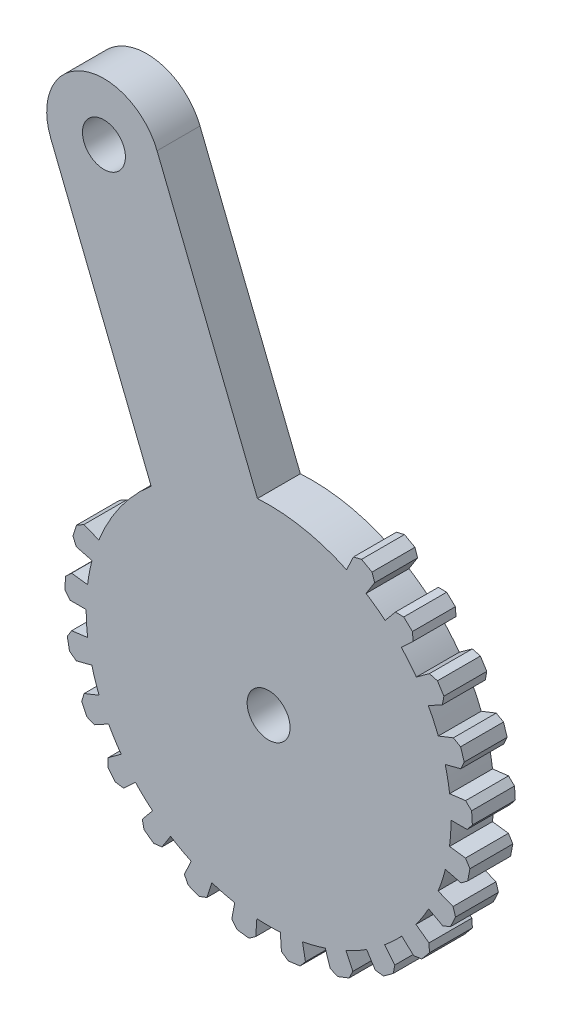
SolidWorks part; units mm, degrees
ref_plane "Front Plane" through (0, 0, 0) normal (0, 0, 1) x (1, 0, 0)
ref_plane "Top Plane" through (0, 0, 0) normal (0, 1, 0) x (1, 0, 0)
ref_plane "Right Plane" through (0, 0, 0) normal (1, 0, 0) x (0, 0, -1)
sketch "Sketch1" plane through (0, 0, 0) normal (0, 0, 1) x (1, 0, 0)
  line L4 (0, 0) -> (-4.7333, 11.8389) construction
  line L5 (0, 0) -> (-11.5084, 28.7847) construction
  line L6 (-8.2085, 9.7562) -> (-15.2225, 27.2997)
  line L7 (-0.7802, 12.7261) -> (-7.7942, 30.2696)
  line L9 (-6.862, 12.482) -> (-6.865, 12.4874) construction
  line L11 (-9.7506, 10.3833) -> (-9.7548, 10.3878) construction
  line L12 (-12.0265, 7.6322) -> (-12.0317, 7.6355) construction
  line L13 (-13.5467, 4.4016) -> (-13.5526, 4.4035) construction
  line L14 (-14.2157, 0.8944) -> (-14.2219, 0.8948) construction
  line L16 (5.4488, 11.5271) -> (5.9296, 12.5441)
  line L17 (7.4141, 11.728) -> (7.2288, 12.2804)
  line L18 (5.9296, 12.5441) -> (6.4953, 12.6836)
  line L19 (6.813, 10.7771) -> (7.4141, 11.728)
  line L20 (6.4953, 12.6836) -> (7.2288, 12.2804)
  line L22 (8.1443, 9.8098) -> (8.8629, 10.6754)
  line L23 (10.0978, 9.5157) -> (10.0557, 10.0968)
  line L24 (8.8629, 10.6754) -> (9.4455, 10.6698)
  line L25 (9.2791, 8.7442) -> (10.0978, 9.5157)
  line L26 (9.4455, 10.6698) -> (10.0557, 10.0968)
  line L28 (10.328, 7.4762) -> (11.2393, 8.1359)
  line L29 (12.1471, 6.7055) -> (12.2507, 7.2789)
  line L30 (11.2393, 8.1359) -> (11.8022, 7.9856)
  line L31 (11.1622, 6.1619) -> (12.1471, 6.7055)
  line L32 (11.8022, 7.9856) -> (12.2507, 7.2789)
  line L34 (11.8628, 4.6729) -> (12.9095, 5.0852)
  line L35 (13.433, 3.474) -> (13.676, 4.0036)
  line L36 (12.9095, 5.0852) -> (13.4174, 4.7996)
  line L37 (12.3439, 3.1923) -> (13.433, 3.474)
  line L38 (13.4174, 4.7996) -> (13.676, 4.0036)
  line L40 (12.6522, 1.5759) -> (13.7686, 1.715)
  line L41 (13.875, 0.0242) -> (14.242, 0.4767)
  line L42 (13.7686, 1.715) -> (14.1895, 1.312)
  line L43 (12.75, 0.0223) -> (13.875, 0.0242)
  line L44 (14.1895, 1.312) -> (14.242, 0.4767)
  line L46 (12.6467, -1.6201) -> (13.7625, -1.763)
  line L47 (13.4451, -3.4271) -> (13.9131, -3.0801)
  line L48 (13.7625, -1.763) -> (14.07, -2.258)
  line L49 (12.355, -3.1492) -> (13.4451, -3.4271)
  line L50 (14.07, -2.258) -> (13.9131, -3.0801)
  line L52 (11.8464, -4.7143) -> (12.8917, -5.1302)
  line L53 (12.1704, -6.6631) -> (12.71, -6.4434)
  line L54 (12.8917, -5.1302) -> (13.0664, -5.6861)
  line L55 (11.1836, -6.1228) -> (12.1704, -6.6631)
  line L56 (13.0664, -5.6861) -> (12.71, -6.4434)
  line L58 (10.3019, -7.5123) -> (11.2109, -8.1751)
  line L59 (10.131, -9.4804) -> (10.7083, -9.4018)
  line L60 (11.2109, -8.1751) -> (11.2418, -8.7569)
  line L61 (9.3096, -8.7117) -> (10.131, -9.4804)
  line L62 (11.2418, -8.7569) -> (10.7083, -9.4018)
  line L64 (8.11, -9.8382) -> (8.8256, -10.7063)
  line L65 (7.455, -11.7021) -> (8.0338, -11.7695)
  line L66 (8.8256, -10.7063) -> (8.7109, -11.2775)
  line L67 (6.8506, -10.7532) -> (7.455, -11.7021)
  line L68 (8.7109, -11.2775) -> (8.0338, -11.7695)
  line L70 (5.4085, -11.546) -> (5.8858, -12.5648)
  line L71 (4.3106, -13.1884) -> (4.8544, -13.3977)
  line L72 (5.8858, -12.5648) -> (5.6326, -13.0895)
  line L73 (3.9611, -12.1191) -> (4.3106, -13.1884)
  line L74 (5.6326, -13.0895) -> (4.8544, -13.3977)
  line L76 (2.3672, -12.5283) -> (2.5761, -13.6338)
  line L77 (0.8954, -13.8461) -> (1.37, -14.184)
  line L78 (2.5761, -13.6338) -> (2.2004, -14.0791)
  line L79 (0.8228, -12.7234) -> (0.8954, -13.8461)
  line L80 (2.2004, -14.0791) -> (1.37, -14.184)
  line L82 (-0.8228, -12.7234) -> (-0.8954, -13.8461)
  line L83 (-2.5761, -13.6338) -> (-2.2004, -14.0791)
  line L84 (-0.8954, -13.8461) -> (-1.37, -14.184)
  line L85 (-2.3672, -12.5283) -> (-2.5761, -13.6338)
  line L86 (-1.37, -14.184) -> (-2.2004, -14.0791)
  line L88 (-3.9611, -12.1191) -> (-4.3106, -13.1884)
  line L89 (-5.8858, -12.5648) -> (-5.6326, -13.0895)
  line L90 (-4.3106, -13.1884) -> (-4.8544, -13.3977)
  line L91 (-5.4085, -11.546) -> (-5.8858, -12.5648)
  line L92 (-4.8544, -13.3977) -> (-5.6326, -13.0895)
  line L94 (-6.8506, -10.7532) -> (-7.455, -11.7021)
  line L95 (-8.8256, -10.7063) -> (-8.7109, -11.2775)
  line L96 (-7.455, -11.7021) -> (-8.0338, -11.7695)
  line L97 (-8.11, -9.8382) -> (-8.8256, -10.7063)
  line L98 (-8.0338, -11.7695) -> (-8.7109, -11.2775)
  line L100 (-9.3096, -8.7117) -> (-10.131, -9.4804)
  line L101 (-11.2109, -8.1751) -> (-11.2418, -8.7569)
  line L102 (-10.131, -9.4804) -> (-10.7083, -9.4018)
  line L103 (-10.3019, -7.5123) -> (-11.2109, -8.1751)
  line L104 (-10.7083, -9.4018) -> (-11.2418, -8.7569)
  line L106 (-11.1836, -6.1228) -> (-12.1704, -6.6631)
  line L107 (-12.8917, -5.1302) -> (-13.0664, -5.6861)
  line L108 (-12.1704, -6.6631) -> (-12.71, -6.4434)
  line L109 (-11.8464, -4.7143) -> (-12.8917, -5.1302)
  line L110 (-12.71, -6.4434) -> (-13.0664, -5.6861)
  line L112 (-12.355, -3.1492) -> (-13.4451, -3.4271)
  line L113 (-13.7625, -1.763) -> (-14.07, -2.258)
  line L114 (-13.4451, -3.4271) -> (-13.9131, -3.0801)
  line L115 (-12.6467, -1.6201) -> (-13.7625, -1.763)
  line L116 (-13.9131, -3.0801) -> (-14.07, -2.258)
  line L118 (-12.75, 0.0223) -> (-13.875, 0.0242)
  line L119 (-13.7686, 1.715) -> (-14.1895, 1.312)
  line L120 (-13.875, 0.0242) -> (-14.242, 0.4767)
  line L121 (-12.6522, 1.5759) -> (-13.7686, 1.715)
  line L122 (-14.242, 0.4767) -> (-14.1895, 1.312)
  line L124 (-12.3439, 3.1923) -> (-13.433, 3.474)
  line L125 (-12.9095, 5.0852) -> (-13.4174, 4.7996)
  line L126 (-13.433, 3.474) -> (-13.676, 4.0036)
  line L127 (-11.8628, 4.6729) -> (-12.9095, 5.0852)
  line L128 (-13.676, 4.0036) -> (-13.4174, 4.7996)
  line L148 (-13.9916, -2.669) -> (-13.9976, -2.6702) construction
  line L149 (-12.8882, -6.0647) -> (-12.8938, -6.0674) construction
  line L150 (-10.9751, -9.0794) -> (-10.9798, -9.0833) construction
  circle A10 centre (0, 0) radius 1.5
  arc A17 (8.1443, 9.8098) -> (6.813, 10.7771) centre (0, 0) ccw
  arc A18 (-0.8228, -12.7234) -> (0.8228, -12.7234) centre (0, 0) ccw
  arc A19 (-3.9611, -12.1191) -> (-2.3672, -12.5283) centre (0, 0) ccw
  arc A20 (10.328, 7.4762) -> (9.2791, 8.7442) centre (0, 0) ccw
  arc A22 (11.8628, 4.6729) -> (11.1622, 6.1619) centre (0, 0) ccw
  arc A23 (-7.7942, 30.2696) -> (-15.2225, 27.2997) centre (-11.5084, 28.7847) ccw
  arc A24 (12.6522, 1.5759) -> (12.3439, 3.1923) centre (0, 0) ccw
  arc A25 (5.4488, 11.5271) -> (-0.7802, 12.7261) centre (0, 0) ccw
  arc A26 (12.6467, -1.6201) -> (12.75, 0.0223) centre (0, 0) ccw
  arc A27 (-8.2085, 9.7562) -> (-11.8628, 4.6729) centre (0, 0) ccw
  circle A28 centre (-11.5084, 28.7847) radius 1.5
  arc A29 (11.8464, -4.7143) -> (12.355, -3.1492) centre (0, 0) ccw
  arc A30 (5.4488, 11.5271) -> (4, 12.1063) centre (0, 0) ccw
  arc A31 (10.3019, -7.5123) -> (11.1836, -6.1228) centre (0, 0) ccw
  arc A34 (-13.4174, 4.7996) -> (-13.676, 4.0036) centre (0, 0) ccw
  arc A35 (-14.1895, 1.312) -> (-14.242, 0.4767) centre (0, 0) ccw
  arc A36 (-14.07, -2.258) -> (-13.9131, -3.0801) centre (0, 0) ccw
  arc A37 (-13.0664, -5.6861) -> (-12.71, -6.4434) centre (0, 0) ccw
  arc A38 (-10.9798, -9.0833) -> (-10.7083, -9.4018) centre (0, 0) ccw
  arc A45 (8.1443, 9.8098) -> (6.813, 10.7771) centre (0, 0) ccw
  arc A46 (8.11, -9.8382) -> (9.3096, -8.7117) centre (0, 0) ccw
  arc A47 (5.4085, -11.546) -> (6.8506, -10.7532) centre (0, 0) ccw
  arc A48 (2.3672, -12.5283) -> (3.9611, -12.1191) centre (0, 0) ccw
  arc A49 (-0.8228, -12.7234) -> (0.8228, -12.7234) centre (0, 0) ccw
  arc A50 (-6.8506, -10.7532) -> (-5.4085, -11.546) centre (0, 0) ccw
  arc A51 (-9.3096, -8.7117) -> (-8.11, -9.8382) centre (0, 0) ccw
  arc A52 (-11.1836, -6.1228) -> (-10.3019, -7.5123) centre (0, 0) ccw
  arc A53 (-12.355, -3.1492) -> (-11.8464, -4.7143) centre (0, 0) ccw
  arc A54 (-12.75, 0.0223) -> (-12.6467, -1.6201) centre (0, 0) ccw
  arc A55 (-12.3439, 3.1923) -> (-12.6522, 1.5759) centre (0, 0) ccw
  arc A56 (-11.1622, 6.1619) -> (-11.8628, 4.6729) centre (0, 0) ccw
  point P4 (0, 15.5)
  point P13 (-5.7542, 14.3923)
  point P183 (0, 0)
  dimension "D1" = 3
  dimension "D3" = 31
  dimension "D4" = 8
extrude "Boss-Extrude2" add sketch "Sketch1" along normal blind 3
